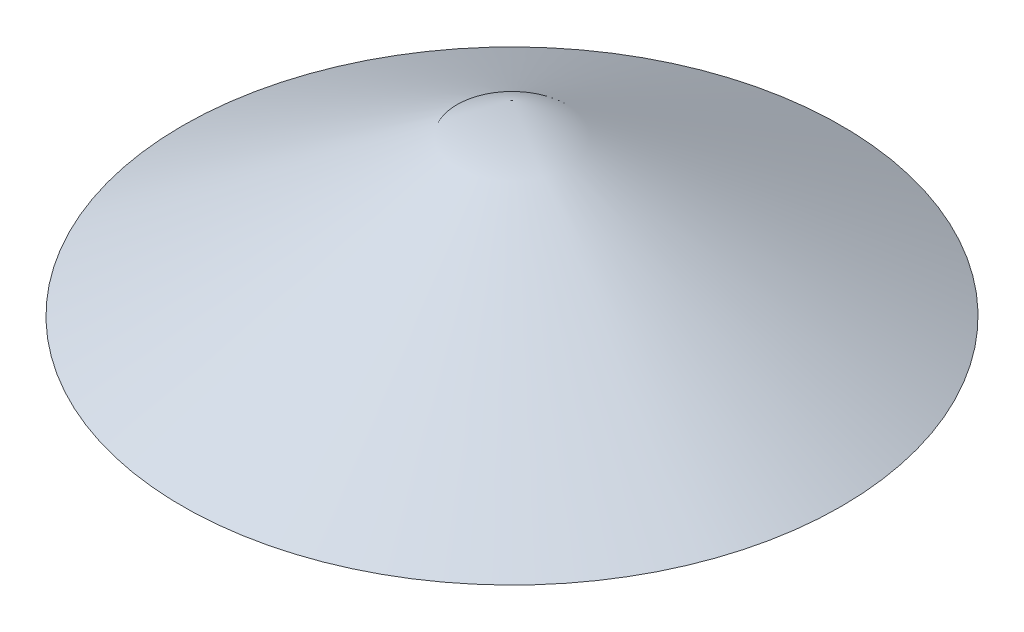
SolidWorks part; units mm, degrees
ref_plane "Front Plane" through (0, 0, 0) normal (0, 0, 1) x (1, 0, 0)
ref_plane "Top Plane" through (0, 0, 0) normal (0, 1, 0) x (1, 0, 0)
ref_plane "Right Plane" through (0, 0, 0) normal (1, 0, 0) x (0, 0, -1)
sketch "Sketch1" plane through (0, 0, 0) normal (0, 0, 1) x (1, 0, 0)
  line L0 (0, 0) -> (30, 0)
  line L1 (30, 0) -> (0, 17)
  line L2 (0, 17) -> (0, 0)
  dimension "D1" = 17
  dimension "D2" = 30
revolve "Revolve1" add sketch "Sketch1" angle 360 about L2
